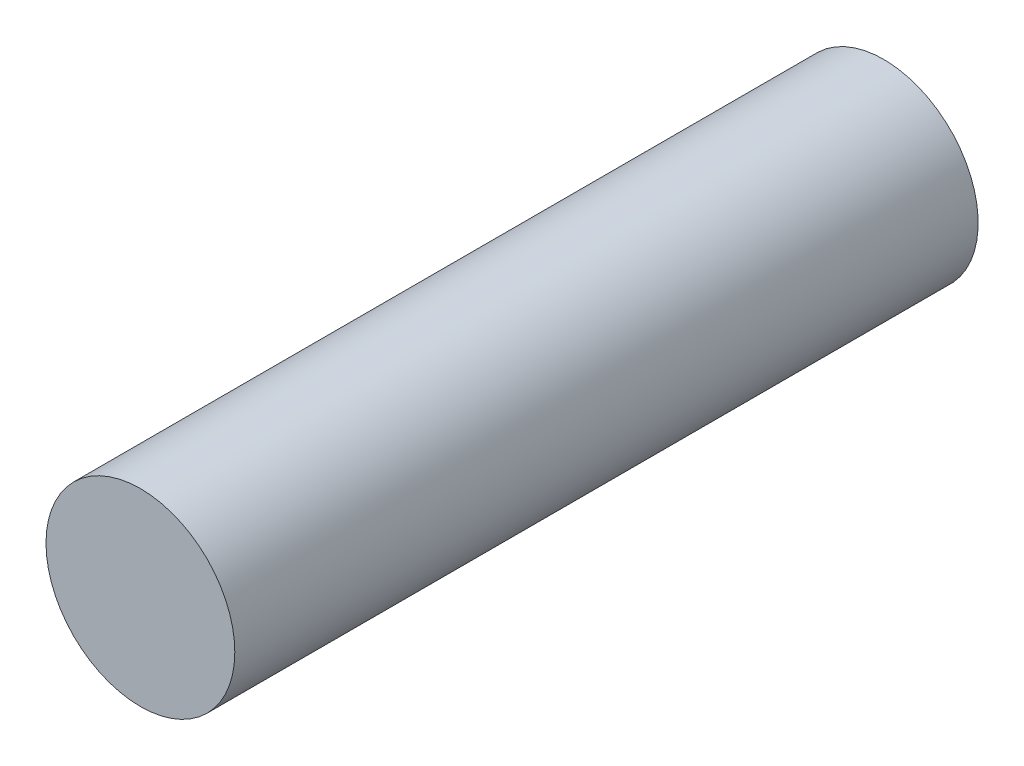
SolidWorks part; units mm, degrees
ref_plane "Front Plane" through (0, 0, 0) normal (0, 0, 1) x (1, 0, 0)
ref_plane "Top Plane" through (0, 0, 0) normal (0, 1, 0) x (1, 0, 0)
ref_plane "Right Plane" through (0, 0, 0) normal (1, 0, 0) x (0, 0, -1)
sketch "Sketch1" plane through (0, 0, 0) normal (0, 0, 1) x (1, 0, 0)
  circle A0 centre (0, 0) radius 12.7
extrude "Boss-Extrude1" add sketch "Sketch1" along normal blind 75
sketch "Sketch2" plane through (0, 0, 0) normal (0, 0, -1) x (-1, 0, 0)
  circle A0 centre (0, 0) radius 9
  circle A1 centre (0, 0) radius 12.7
extrude "Boss-Extrude2" add sketch "Sketch2" along normal blind 25
